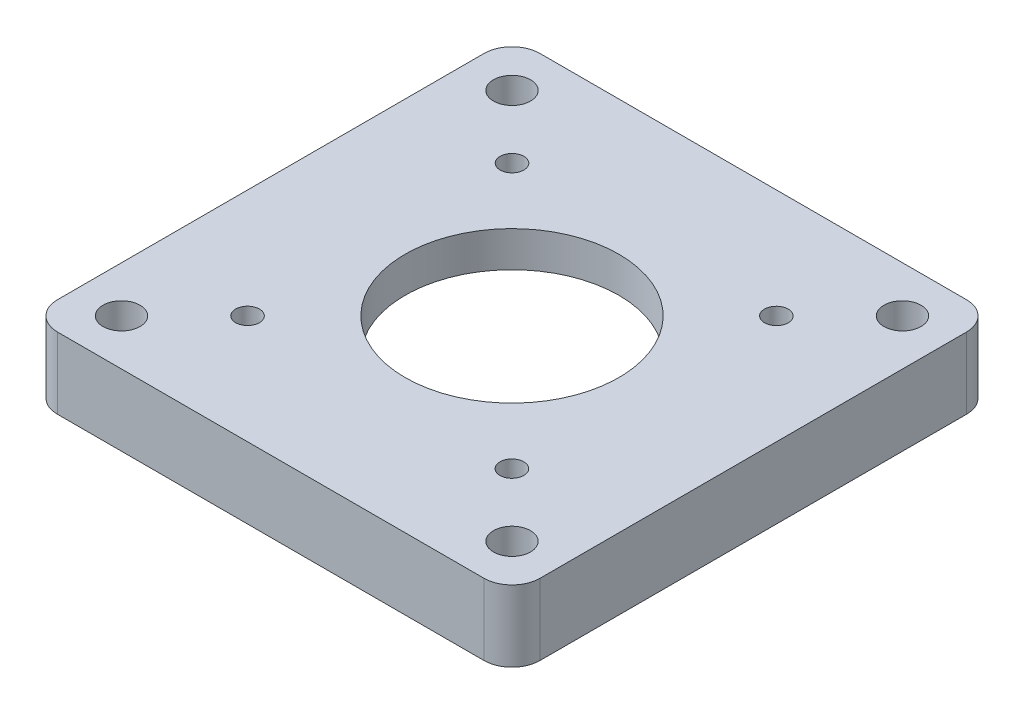
SolidWorks part; units mm, degrees
ref_plane "Front Plane" through (0, 0, 0) normal (0, 0, 1) x (1, 0, 0)
ref_plane "Top Plane" through (0, 0, 0) normal (0, 1, 0) x (1, 0, 0)
ref_plane "Right Plane" through (0, 0, 0) normal (1, 0, 0) x (0, 0, -1)
ref_plane "Plane1" through (0, 6.35, 0) normal (0, 1, 0) x (1, 0, 0)
sketch "Sketch1" plane through (0, 6.35, 0) normal (0, 1, 0) x (1, 0, 0)
  line L0 (-43, 43) -> (-43, -43)
  line L1 (-43, -43) -> (43, -43)
  line L2 (43, -43) -> (43, 43)
  line L3 (43, 43) -> (-43, 43)
extrude "Boss-Extrude1" add sketch "Sketch1" against normal blind 12.7
sketch "Sketch2" plane through (0, -6.35, 0) normal (0, -1, 0) x (1, 0, 0)
  arc A0 (-30.3196, -20.3217) -> (-20.3217, -30.3196) centre (-23.55, -23.55) ccw
  arc A1 (-20.3217, -30.3196) -> (20.3217, -30.3196) centre (0, 0) ccw
  arc A2 (20.3217, -30.3196) -> (30.3196, -20.3217) centre (23.55, -23.55) ccw
  arc A3 (30.3196, -20.3217) -> (30.3196, 20.3217) centre (0, 0) ccw
  arc A4 (30.3196, 20.3217) -> (20.3217, 30.3196) centre (23.55, 23.55) ccw
  arc A5 (20.3217, 30.3196) -> (-20.3217, 30.3196) centre (0, 0) ccw
  arc A6 (-20.3217, 30.3196) -> (-30.3196, 20.3217) centre (-23.55, 23.55) ccw
  arc A7 (-30.3196, 20.3217) -> (-30.3196, -20.3217) centre (0, 0) ccw
extrude "Cut-Extrude1" cut sketch "Sketch2" against normal blind 6.35
hole_wizard "Ø6.6 (6.6) Diameter Hole1" positions "Sketch4" profile "Sketch3" hole size "Ø6.6" standard "ANSI Metric"
sketch "Sketch4" plane through (0, -6.35, 0) normal (0, -1, 0) x (-1, 0, 0)
  point P0 (-34.8, 34.8)
  point P1 (-34.8, -34.8)
  point P2 (34.8, -34.8)
  point P3 (34.8, 34.8)
sketch "Sketch3" plane through (34.8, -6.35, -34.8) normal (1, 0, 0) x (0, 0, -1)
  line L0 (0, 0) -> (0, 12.7)
  line L1 (0, 12.7) -> (3.3, 12.7)
  line L2 (3.3, 12.7) -> (3.3, 0)
  line L5 (3.3, 0) -> (0, 0)
  line L11 (0, -6.35) -> (0, 107.95) construction
  dimension "Thru Hole Dia." = 6.6
  dimension "Thru Hole Depth" = 12.7
hole_wizard "Hole1" positions "Sketch6" profile "Sketch5" legacy end condition through all
sketch "Sketch6" plane through (0, 0, 0) normal (0, -1, 0) x (-1, 0, 0)
  point P0 (23.57, -23.57)
  point P1 (-23.57, 23.55)
  point P2 (-23.57, -23.59)
  point P3 (23.57, 23.57)
  point P9 (-63.264, 29.4893)
  point P10 (0, 0)
  point P11 (0, 0)
  dimension "D1" = 47.14
  dimension "D2" = 47.14
  dimension "D3" = 47.14
  dimension "D4" = 23.57
  dimension "D5" = 23.57
sketch "Sketch5" plane through (-23.57, 0, 23.57) normal (1, 0, 0) x (0, 0, -1)
  line L0 (0, 0) -> (0, 6.35)
  line L1 (0, 6.35) -> (2.117, 6.35)
  line L2 (2.117, 6.35) -> (2.117, 0)
  line L3 (2.117, 0) -> (0, 0)
  line L4 (0, 110) -> (0, -10) construction
  dimension "Diameter" = 4.234
  dimension "Depth" = 6.35
hole_wizard "M36 Clearance Hole1" positions "Sketch8" profile "Sketch7" hole size "M36" standard "ANSI Metric"
sketch "Sketch8" plane through (0, 6.35, 0) normal (0, 1, 0) x (1, 0, 0)
  point P0 (0, 0)
sketch "Sketch7" plane through (0, 6.35, 0) normal (1, 0, 0) x (0, 0, 1)
  line L0 (0, 0) -> (0, 12.7)
  line L1 (0, 12.7) -> (19.05, 12.7)
  line L2 (19.05, 12.7) -> (19.05, 0)
  line L5 (19.05, 0) -> (0, 0)
  line L11 (0, -6.35) -> (0, 107.95) construction
  dimension "Thru Hole Dia." = 38.1
  dimension "Thru Hole Depth" = 12.7
fillet "Fillet1" radius 5 4 edges at (-43, 0, 43) (43, 0, 43) (-43, 0, -43) (43, 0, -43)
